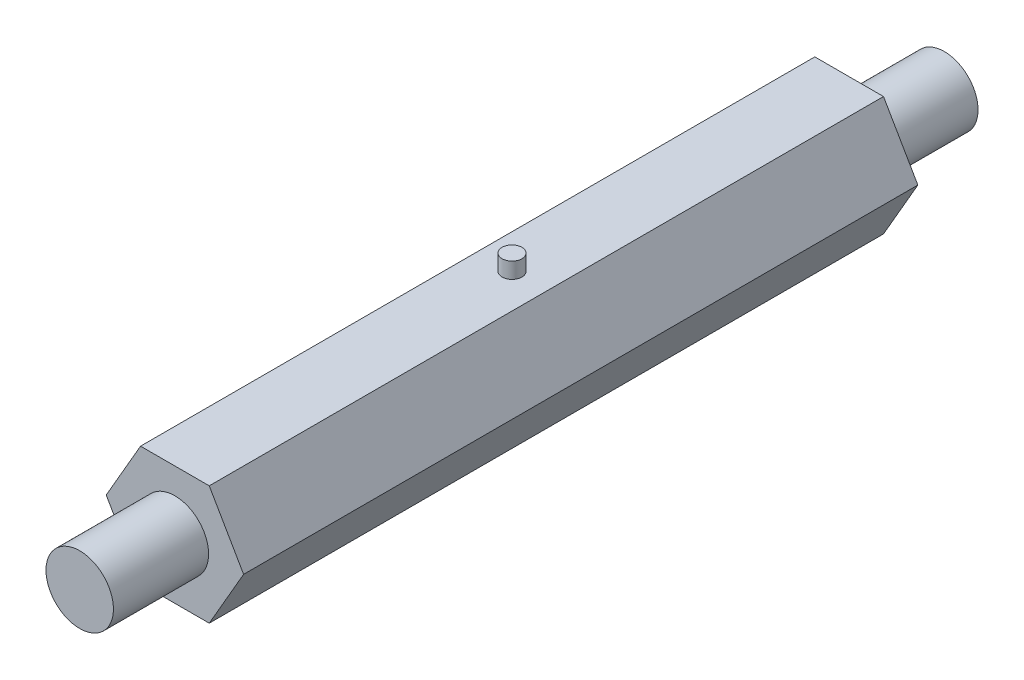
SolidWorks part; units mm, degrees
ref_plane "Front Plane" through (0, 0, 0) normal (0, 0, 1) x (1, 0, 0)
ref_plane "Top Plane" through (0, 0, 0) normal (0, 1, 0) x (1, 0, 0)
ref_plane "Right Plane" through (0, 0, 0) normal (1, 0, 0) x (0, 0, -1)
sketch "Sketch1" plane through (0, 0, 0) normal (0, 0, 1) x (1, 0, 0)
  line L1 (5.4993, 9.525) -> (-5.4993, 9.525)
  line L2 (-5.4993, 9.525) -> (-10.9985, 0)
  line L3 (-10.9985, 0) -> (-5.4993, -9.525)
  line L4 (-5.4993, -9.525) -> (5.4993, -9.525)
  line L5 (5.4993, -9.525) -> (10.9985, 0)
  line L6 (10.9985, 0) -> (5.4993, 9.525)
  circle A0 centre (0, 0) radius 9.525 construction
  dimension "D1" = 19.05
extrude "Boss-Extrude1" add sketch "Sketch1" along normal blind 53.975
sketch "Sketch2" plane through (0, 0, 53.975) normal (0, 0, 1) x (1, 0, 0)
  circle A0 centre (0, 0) radius 5.3975
  dimension "D1" = 10.795
extrude "Boss-Extrude2" add sketch "Sketch2" along normal blind 15.24
mirror "Mirror1" about plane through (0, 0, 0) normal (0, 0, 1) of bodies 102
sketch "Sketch3" plane through (0, 9.525, 0) normal (0, 1, 0) x (1, 0, 0)
  circle A0 centre (0, 0) radius 1.5875
  dimension "D1" = 3.175
extrude "Boss-Extrude3" add sketch "Sketch3" along normal blind 2.54
